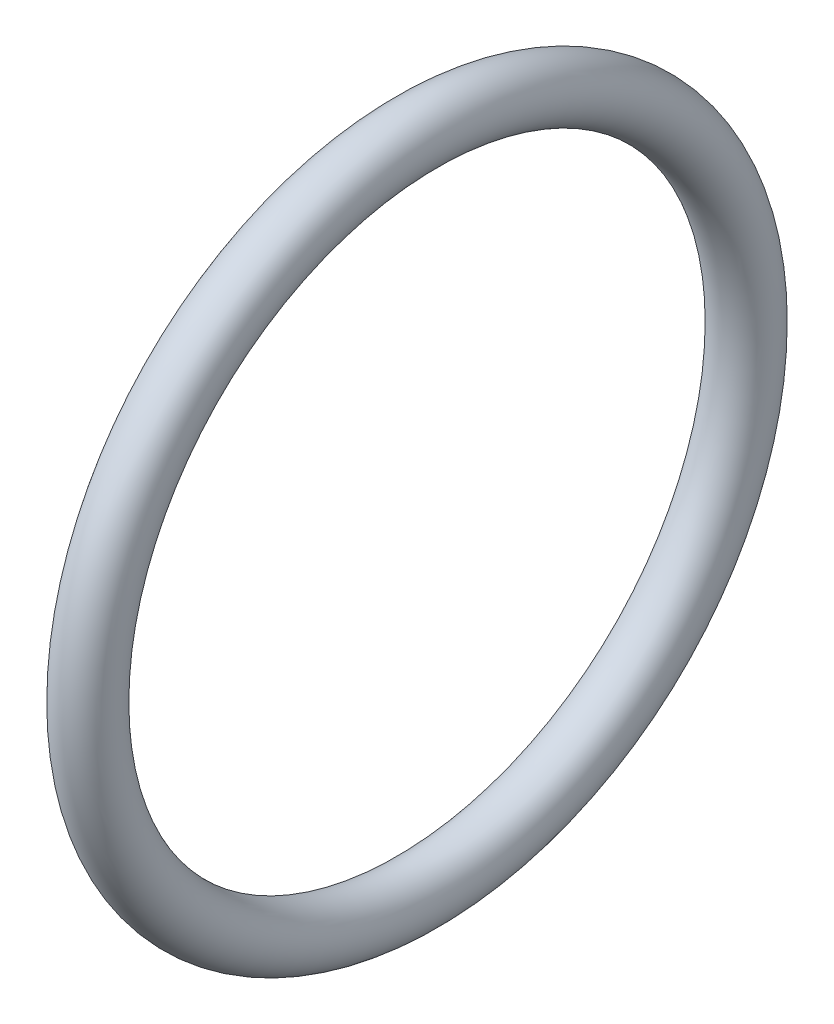
SolidWorks part; units mm, degrees
material "HYPALON"
ref_plane "Front Plane" through (0, 0, 0) normal (0, 0, 1) x (1, 0, 0)
ref_plane "Top Plane" through (0, 0, 0) normal (0, 1, 0) x (1, 0, 0)
ref_plane "Right Plane" through (0, 0, 0) normal (1, 0, 0) x (0, 0, -1)
sketch "Sketch2" plane through (0, 0, 0) normal (0, 0, 1) x (1, 0, 0)
  line L0 (0, 0) -> (15.7303, 0) construction
  circle A0 centre (0, 18) radius 1.5875
  dimension "D1" = 3.175
  dimension "D2" = 18
revolve "Revolve1" add sketch "Sketch2" angle 360 about L0
